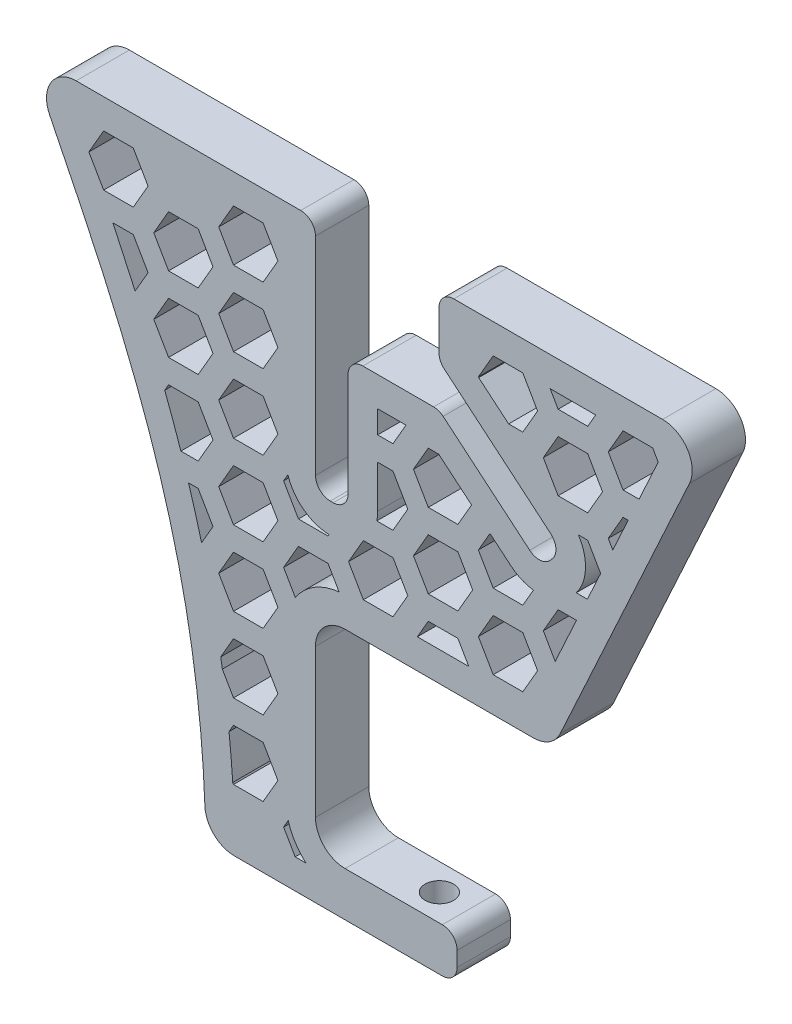
SolidWorks part; units mm, degrees
ref_plane "Front Plane" through (0, 0, 0) normal (0, 0, 1) x (1, 0, 0)
ref_plane "Top Plane" through (0, 0, 0) normal (0, 1, 0) x (1, 0, 0)
ref_plane "Right Plane" through (0, 0, 0) normal (1, 0, 0) x (0, 0, -1)
sketch "Sketch1" plane through (0, 0, 0) normal (0, 0, 1) x (1, 0, 0)
  line L0 (0, -10) -> (0, -60)
  line L1 (10, 0) -> (73.5896, 0)
  line L2 (82.6764, 5.825) -> (126.325, 100.825)
  line L3 (132.8378, 115) -> (-37.1622, 115) construction
  line L4 (-37.1622, 115) -> (-80.8457, 115)
  line L5 (-37.1622, 115) -> (-37.1622, -85) construction
  line L6 (-27.3578, -85) -> (42.8378, -85)
  line L7 (47.8378, -80) -> (47.8378, -75)
  line L8 (42.8378, -70) -> (10, -70)
  line L9 (80, 0) -> (47.8378, -70) construction
  line L10 (0, 0) -> (-37.1622, 0) construction
  line L11 (-89.8011, 100.5501) -> (-65.055, 50.749) construction
  line L12 (-40.3089, 0.948) -> (-37.3503, -75.3873) construction
  line L13 (0, 110) -> (0, 40)
  line L14 (5, 35) -> (6, 35)
  line L15 (11, 40) -> (11, 75)
  line L16 (16, 80) -> (39.8915, 80)
  line L17 (43.1055, 78.8302) -> (72.3532, 54.2885)
  line L18 (79.3973, 54.9048) -> (80.0401, 55.6708)
  line L19 (79.4238, 62.715) -> (43.4974, 92.8608)
  line L20 (41.7114, 96.691) -> (41.7114, 110)
  line L21 (46.7114, 115) -> (117.2382, 115)
  line L22 (41.7114, 80) -> (0, 115) construction
  line L23 (41.7114, 94.3595) -> (41.7114, 80) construction
  line L24 (-5, 115) -> (-37.1622, 115)
  line L25 (-65.055, 50.749) -> (-40.3089, 0.948) construction
  arc A0 (0, -60) -> (10, -70) centre (10, -60) ccw
  arc A1 (0, -10) -> (10, 0) centre (10, -10) cw
  arc A2 (73.5896, 0) -> (82.6764, 5.825) centre (73.5896, 10) ccw
  arc A3 (-27.3578, -85) -> (-37.3503, -75.3873) centre (-27.3578, -75) cw
  arc A4 (126.325, 100.825) -> (117.2382, 115) centre (117.2382, 105) ccw
  arc A5 (-80.8457, 115) -> (-89.8011, 100.5501) centre (-80.8457, 105) ccw
  arc A6 (42.8378, -85) -> (47.8378, -80) centre (42.8378, -80) ccw
  arc A7 (47.8378, -75) -> (42.8378, -70) centre (42.8378, -75) ccw
  arc A8 (0, 40) -> (5, 35) centre (5, 40) ccw
  arc A9 (6, 35) -> (11, 40) centre (6, 40) ccw
  arc A10 (11, 75) -> (16, 80) centre (16, 75) cw
  arc A11 (80.0401, 55.6708) -> (79.4238, 62.715) centre (76.2099, 58.8848) ccw
  arc A12 (72.3532, 54.2885) -> (79.3973, 54.9048) centre (75.5671, 58.1187) ccw
  arc A13 (39.8915, 80) -> (43.1055, 78.8302) centre (39.8915, 75) cw
  arc A14 (43.4974, 92.8608) -> (41.7114, 96.691) centre (46.7114, 96.691) cw
  arc A15 (41.7114, 110) -> (46.7114, 115) centre (46.7114, 110) cw
  arc A16 (0, 110) -> (-5, 115) centre (-5, 110) ccw
  spline S0 degree 3 poles (-89.8011, 100.5501) (-65.055, 50.749) (-40.3089, 0.948) (-37.3503, -75.3873) knots 0 0 0 0 1 1 1 1
  point P20 (0, 0)
  point P22 (0, 0)
  point P23 (0, 0)
  point P26 (0, -70)
  point P44 (47.8378, -85)
  point P50 (0, 35)
  point P53 (11, 35)
  point P56 (11, 80)
  point P59 (83.254, 59.501)
  point P62 (76.1834, 51.0746)
  point P71 (41.7114, 115)
  dimension "D13" = 10
  dimension "D2" = 5
  dimension "D1" = 170
  dimension "D3" = 80
  dimension "D4" = 70
  dimension "D5" = 15
  dimension "D8" = 45
  dimension "D9" = 80
  dimension "D10" = 11
  dimension "D11" = 45
  dimension "D12" = 11
extrude "Boss-Extrude1" add sketch "Sketch1" along normal blind 18
sketch "Sketch2" plane through (0, -70, 0) normal (0, 1, 0) x (1, 0, 0)
  line L0 (32.8378, -9) -> (47.8378, -9) construction
  line L1 (47.8378, -18) -> (47.8378, 0) construction
  circle A0 centre (32.8378, -9) radius 4.8
  dimension "D2" = 9.6
  dimension "D1" = 15
extrude "Cut-Extrude1" cut sketch "Sketch2" against normal through all contours A0
sketch "Sketch3" plane through (0, 0, 18) normal (0, 0, 1) x (1, 0, 0)
  line L0 (-144.2621, 20.3782) -> (-149.2621, 29.0385)
  line L1 (-149.2621, 29.0385) -> (-159.2621, 29.0385)
  line L2 (-159.2621, 29.0385) -> (-164.2621, 20.3782)
  line L3 (-164.2621, 20.3782) -> (-159.2621, 11.718)
  line L4 (-159.2621, 11.718) -> (-149.2621, 11.718)
  line L5 (-149.2621, 11.718) -> (-144.2621, 20.3782)
  line L6 (-122.3339, 7.718) -> (-127.3339, 16.3782)
  line L7 (-127.3339, 16.3782) -> (-137.3339, 16.3782)
  line L8 (-137.3339, 16.3782) -> (-142.3339, 7.718)
  line L9 (-142.3339, 7.718) -> (-137.3339, -0.9423)
  line L10 (-137.3339, -0.9423) -> (-127.3339, -0.9423)
  line L11 (-127.3339, -0.9423) -> (-122.3339, 7.718)
  line L12 (-100.4057, -4.9423) -> (-105.4057, 3.718)
  line L13 (-105.4057, 3.718) -> (-115.4057, 3.718)
  line L14 (-115.4057, 3.718) -> (-120.4057, -4.9423)
  line L15 (-120.4057, -4.9423) -> (-115.4057, -13.6025)
  line L16 (-115.4057, -13.6025) -> (-105.4057, -13.6025)
  line L17 (-166.1903, 33.0385) -> (-171.1903, 41.6987)
  line L18 (-171.1903, 41.6987) -> (-181.1903, 41.6987)
  line L19 (-181.1903, 41.6987) -> (-186.1903, 33.0385)
  line L20 (-186.1903, 33.0385) -> (-181.1903, 24.3782)
  line L21 (-181.1903, 24.3782) -> (-171.1903, 24.3782)
  line L22 (-171.1903, 24.3782) -> (-166.1903, 33.0385)
  line L23 (-105.4057, -13.6025) -> (-100.4057, -4.9423)
  line L24 (-78.4775, -17.6025) -> (-83.4775, -8.9423)
  line L25 (-83.4775, -8.9423) -> (-93.4775, -8.9423)
  line L26 (-93.4775, -8.9423) -> (-98.4775, -17.6025)
  line L27 (-98.4775, -17.6025) -> (-93.4775, -26.2628)
  line L28 (-93.4775, -26.2628) -> (-83.4775, -26.2628)
  line L29 (-83.4775, -26.2628) -> (-78.4775, -17.6025)
  line L30 (-56.5493, -30.2628) -> (-61.5493, -21.6025)
  line L31 (-61.5493, -21.6025) -> (-71.5493, -21.6025)
  line L32 (-10, 105) -> (-80.8457, 105)
  line L33 (-27.3578, -75) -> (-3.2288, -75)
  line L34 (-10, -60) -> (-10, -10)
  line L35 (10, 10) -> (73.5896, 10)
  line L36 (73.5896, 10) -> (117.2382, 105)
  line L37 (117.2382, 105) -> (51.7114, 105)
  line L38 (51.7114, 105) -> (51.7114, 99.0226)
  line L39 (51.7114, 99.0226) -> (85.8517, 70.3754)
  line L40 (87.7005, 49.2429) -> (87.0578, 48.4769)
  line L41 (65.9253, 46.6281) -> (38.0717, 70)
  line L42 (38.0717, 70) -> (21, 70)
  line L43 (21, 70) -> (21, 40)
  line L44 (6, 25) -> (5, 25)
  line L45 (-10, 40) -> (-10, 105)
  line L46 (-10, 105) -> (-80.8457, 105)
  line L47 (-27.3578, -75) -> (-3.2288, -75)
  line L48 (-10, -60) -> (-10, -10)
  line L49 (10, 10) -> (73.5896, 10)
  line L50 (73.5896, 10) -> (117.2382, 105)
  line L51 (117.2382, 105) -> (51.7114, 105)
  line L52 (51.7114, 105) -> (51.7114, 99.0226)
  line L53 (51.7114, 99.0226) -> (85.8517, 70.3754)
  line L54 (87.7005, 49.2429) -> (87.0578, 48.4769)
  line L55 (65.9253, 46.6281) -> (38.0717, 70)
  line L56 (38.0717, 70) -> (21, 70)
  line L57 (21, 70) -> (21, 40)
  line L58 (6, 25) -> (5, 25)
  line L59 (-10, 40) -> (-10, 105)
  line L60 (-71.5493, -21.6025) -> (-76.5493, -30.2628)
  line L61 (-76.5493, -30.2628) -> (-71.5493, -38.923)
  line L62 (-71.5493, -38.923) -> (-61.5493, -38.923)
  line L63 (-61.5493, -38.923) -> (-56.5493, -30.2628)
  line L64 (-34.6211, -42.923) -> (-39.6211, -34.2628)
  line L65 (-39.6211, -34.2628) -> (-49.6211, -34.2628)
  line L66 (-49.6211, -34.2628) -> (-54.6211, -42.923)
  line L67 (-54.6211, -42.923) -> (-49.6211, -51.5833)
  line L68 (-49.6211, -51.5833) -> (-39.6211, -51.5833)
  line L69 (-39.6211, -51.5833) -> (-34.6211, -42.923)
  line L70 (-12.6929, -55.5833) -> (-17.6929, -46.923)
  line L71 (-17.6929, -46.923) -> (-27.6929, -46.923)
  line L72 (-27.6929, -46.923) -> (-32.6929, -55.5833)
  line L73 (-32.6929, -55.5833) -> (-27.6929, -64.2436)
  line L74 (-27.6929, -64.2436) -> (-17.6929, -64.2436)
  line L75 (-17.6929, -64.2436) -> (-12.6929, -55.5833)
  line L76 (9.2353, -68.2436) -> (4.2353, -59.5833)
  line L77 (4.2353, -59.5833) -> (-5.7647, -59.5833)
  line L78 (-5.7647, -59.5833) -> (-10.7647, -68.2436)
  line L79 (-10.7647, -68.2436) -> (-5.7647, -76.9038)
  line L80 (-5.7647, -76.9038) -> (4.2353, -76.9038)
  line L81 (4.2353, -76.9038) -> (9.2353, -68.2436)
  line L82 (31.1635, -80.9038) -> (26.1635, -72.2436)
  line L83 (26.1635, -72.2436) -> (16.1635, -72.2436)
  line L84 (16.1635, -72.2436) -> (11.1635, -80.9038)
  line L85 (11.1635, -80.9038) -> (16.1635, -89.5641)
  line L86 (16.1635, -89.5641) -> (26.1635, -89.5641)
  line L87 (26.1635, -89.5641) -> (31.1635, -80.9038)
  line L88 (-122.3339, 33.0385) -> (-127.3339, 41.6987)
  line L89 (-127.3339, 41.6987) -> (-137.3339, 41.6987)
  line L90 (-137.3339, 41.6987) -> (-142.3339, 33.0385)
  line L91 (-142.3339, 33.0385) -> (-137.3339, 24.3782)
  line L92 (-137.3339, 24.3782) -> (-127.3339, 24.3782)
  line L93 (-127.3339, 24.3782) -> (-122.3339, 33.0385)
  line L94 (-100.4057, 20.3782) -> (-105.4057, 29.0385)
  line L95 (-105.4057, 29.0385) -> (-115.4057, 29.0385)
  line L96 (-115.4057, 29.0385) -> (-120.4057, 20.3782)
  line L97 (-120.4057, 20.3782) -> (-115.4057, 11.718)
  line L98 (-115.4057, 11.718) -> (-105.4057, 11.718)
  line L99 (-105.4057, 11.718) -> (-100.4057, 20.3782)
  line L100 (-78.4775, 7.718) -> (-83.4775, 16.3782)
  line L101 (-83.4775, 16.3782) -> (-93.4775, 16.3782)
  line L102 (-93.4775, 16.3782) -> (-98.4775, 7.718)
  line L103 (-98.4775, 7.718) -> (-93.4775, -0.9423)
  line L104 (-93.4775, -0.9423) -> (-83.4775, -0.9423)
  line L105 (-144.2621, 45.6987) -> (-149.2621, 54.359)
  line L106 (-149.2621, 54.359) -> (-159.2621, 54.359)
  line L107 (-159.2621, 54.359) -> (-164.2621, 45.6987)
  line L108 (-164.2621, 45.6987) -> (-159.2621, 37.0385)
  line L109 (-159.2621, 37.0385) -> (-149.2621, 37.0385)
  line L110 (-149.2621, 37.0385) -> (-144.2621, 45.6987)
  line L111 (-83.4775, -0.9423) -> (-78.4775, 7.718)
  line L112 (-56.5493, -4.9423) -> (-61.5493, 3.718)
  line L113 (-61.5493, 3.718) -> (-71.5493, 3.718)
  line L114 (-71.5493, 3.718) -> (-76.5493, -4.9423)
  line L115 (-76.5493, -4.9423) -> (-71.5493, -13.6025)
  line L116 (-71.5493, -13.6025) -> (-61.5493, -13.6025)
  line L117 (-61.5493, -13.6025) -> (-56.5493, -4.9423)
  line L118 (-34.6211, -17.6025) -> (-39.6211, -8.9423)
  line L119 (-39.6211, -8.9423) -> (-49.6211, -8.9423)
  line L120 (-49.6211, -8.9423) -> (-54.6211, -17.6025)
  line L121 (-54.6211, -17.6025) -> (-49.6211, -26.2628)
  line L122 (-49.6211, -26.2628) -> (-39.6211, -26.2628)
  line L123 (-39.6211, -26.2628) -> (-34.6211, -17.6025)
  line L124 (-12.6929, -30.2628) -> (-17.6929, -21.6025)
  line L125 (-17.6929, -21.6025) -> (-27.6929, -21.6025)
  line L126 (-27.6929, -21.6025) -> (-32.6929, -30.2628)
  line L127 (-32.6929, -30.2628) -> (-27.6929, -38.923)
  line L128 (-27.6929, -38.923) -> (-17.6929, -38.923)
  line L129 (-17.6929, -38.923) -> (-12.6929, -30.2628)
  line L130 (9.2353, -42.923) -> (4.2353, -34.2628)
  line L131 (4.2353, -34.2628) -> (-5.7647, -34.2628)
  line L132 (-5.7647, -34.2628) -> (-10.7647, -42.923)
  line L133 (-10.7647, -42.923) -> (-5.7647, -51.5833)
  line L134 (-5.7647, -51.5833) -> (4.2353, -51.5833)
  line L135 (4.2353, -51.5833) -> (9.2353, -42.923)
  line L136 (31.1635, -55.5833) -> (26.1635, -46.923)
  line L137 (26.1635, -46.923) -> (16.1635, -46.923)
  line L138 (16.1635, -46.923) -> (11.1635, -55.5833)
  line L139 (11.1635, -55.5833) -> (16.1635, -64.2436)
  line L140 (16.1635, -64.2436) -> (26.1635, -64.2436)
  line L141 (26.1635, -64.2436) -> (31.1635, -55.5833)
  line L142 (53.0917, -68.2436) -> (48.0917, -59.5833)
  line L143 (48.0917, -59.5833) -> (38.0917, -59.5833)
  line L144 (38.0917, -59.5833) -> (33.0917, -68.2436)
  line L145 (33.0917, -68.2436) -> (38.0917, -76.9038)
  line L146 (38.0917, -76.9038) -> (48.0917, -76.9038)
  line L147 (48.0917, -76.9038) -> (53.0917, -68.2436)
  line L148 (-100.4057, 45.6987) -> (-105.4057, 54.359)
  line L149 (-105.4057, 54.359) -> (-115.4057, 54.359)
  line L150 (-115.4057, 54.359) -> (-120.4057, 45.6987)
  line L151 (-120.4057, 45.6987) -> (-115.4057, 37.0385)
  line L152 (-115.4057, 37.0385) -> (-105.4057, 37.0385)
  line L153 (-105.4057, 37.0385) -> (-100.4057, 45.6987)
  line L154 (-78.4775, 33.0385) -> (-83.4775, 41.6987)
  line L155 (-83.4775, 41.6987) -> (-93.4775, 41.6987)
  line L156 (-93.4775, 41.6987) -> (-98.4775, 33.0385)
  line L157 (-98.4775, 33.0385) -> (-93.4775, 24.3782)
  line L158 (-93.4775, 24.3782) -> (-83.4775, 24.3782)
  line L159 (-83.4775, 24.3782) -> (-78.4775, 33.0385)
  line L160 (-56.5493, 20.3782) -> (-61.5493, 29.0385)
  line L161 (-61.5493, 29.0385) -> (-71.5493, 29.0385)
  line L162 (-71.5493, 29.0385) -> (-76.5493, 20.3782)
  line L163 (-76.5493, 20.3782) -> (-71.5493, 11.718)
  line L164 (-71.5493, 11.718) -> (-61.5493, 11.718)
  line L165 (-122.3339, 58.359) -> (-127.3339, 67.0192)
  line L166 (-127.3339, 67.0192) -> (-137.3339, 67.0192)
  line L167 (-137.3339, 67.0192) -> (-142.3339, 58.359)
  line L168 (-142.3339, 58.359) -> (-137.3339, 49.6987)
  line L169 (-137.3339, 49.6987) -> (-127.3339, 49.6987)
  line L170 (-127.3339, 49.6987) -> (-122.3339, 58.359)
  line L171 (-61.5493, 11.718) -> (-56.5493, 20.3782)
  line L172 (-34.6211, 7.718) -> (-39.6211, 16.3782)
  line L173 (-39.6211, 16.3782) -> (-49.6211, 16.3782)
  line L174 (-49.6211, 16.3782) -> (-54.6211, 7.718)
  line L175 (-54.6211, 7.718) -> (-49.6211, -0.9423)
  line L176 (-49.6211, -0.9423) -> (-39.6211, -0.9423)
  line L177 (-39.6211, -0.9423) -> (-34.6211, 7.718)
  line L178 (-12.6929, -4.9423) -> (-17.6929, 3.718)
  line L179 (-17.6929, 3.718) -> (-27.6929, 3.718)
  line L180 (-27.6929, 3.718) -> (-32.6929, -4.9423)
  line L181 (-32.6929, -4.9423) -> (-27.6929, -13.6025)
  line L182 (-27.6929, -13.6025) -> (-17.6929, -13.6025)
  line L183 (-17.6929, -13.6025) -> (-12.6929, -4.9423)
  line L184 (9.2353, -17.6025) -> (4.2353, -8.9423)
  line L185 (4.2353, -8.9423) -> (-5.7647, -8.9423)
  line L186 (-5.7647, -8.9423) -> (-10.7647, -17.6025)
  line L187 (-10.7647, -17.6025) -> (-5.7647, -26.2628)
  line L188 (-5.7647, -26.2628) -> (4.2353, -26.2628)
  line L189 (4.2353, -26.2628) -> (9.2353, -17.6025)
  line L190 (31.1635, -30.2628) -> (26.1635, -21.6025)
  line L191 (26.1635, -21.6025) -> (16.1635, -21.6025)
  line L192 (16.1635, -21.6025) -> (11.1635, -30.2628)
  line L193 (11.1635, -30.2628) -> (16.1635, -38.923)
  line L194 (16.1635, -38.923) -> (26.1635, -38.923)
  line L195 (26.1635, -38.923) -> (31.1635, -30.2628)
  line L196 (53.0917, -42.923) -> (48.0917, -34.2628)
  line L197 (48.0917, -34.2628) -> (38.0917, -34.2628)
  line L198 (38.0917, -34.2628) -> (33.0917, -42.923)
  line L199 (33.0917, -42.923) -> (38.0917, -51.5833)
  line L200 (38.0917, -51.5833) -> (48.0917, -51.5833)
  line L201 (48.0917, -51.5833) -> (53.0917, -42.923)
  line L202 (75.0199, -55.5833) -> (70.0199, -46.923)
  line L203 (70.0199, -46.923) -> (60.0199, -46.923)
  line L204 (60.0199, -46.923) -> (55.0199, -55.5833)
  line L205 (55.0199, -55.5833) -> (60.0199, -64.2436)
  line L206 (60.0199, -64.2436) -> (70.0199, -64.2436)
  line L207 (70.0199, -64.2436) -> (75.0199, -55.5833)
  line L208 (-78.4775, 58.359) -> (-83.4775, 67.0192)
  line L209 (-83.4775, 67.0192) -> (-93.4775, 67.0192)
  line L210 (-93.4775, 67.0192) -> (-98.4775, 58.359)
  line L211 (-98.4775, 58.359) -> (-93.4775, 49.6987)
  line L212 (-93.4775, 49.6987) -> (-83.4775, 49.6987)
  line L213 (-83.4775, 49.6987) -> (-78.4775, 58.359)
  line L214 (-56.5493, 45.6987) -> (-61.5493, 54.359)
  line L215 (-61.5493, 54.359) -> (-71.5493, 54.359)
  line L216 (-71.5493, 54.359) -> (-76.5493, 45.6987)
  line L217 (-76.5493, 45.6987) -> (-71.5493, 37.0385)
  line L218 (-71.5493, 37.0385) -> (-61.5493, 37.0385)
  line L219 (-61.5493, 37.0385) -> (-56.5493, 45.6987)
  line L220 (-34.6211, 33.0385) -> (-39.6211, 41.6987)
  line L221 (-39.6211, 41.6987) -> (-49.6211, 41.6987)
  line L222 (-49.6211, 41.6987) -> (-54.6211, 33.0385)
  line L223 (-54.6211, 33.0385) -> (-49.6211, 24.3782)
  line L224 (-49.6211, 24.3782) -> (-39.6211, 24.3782)
  line L225 (-100.4057, 71.0192) -> (-105.4057, 79.6795)
  line L226 (-105.4057, 79.6795) -> (-115.4057, 79.6795)
  line L227 (-115.4057, 79.6795) -> (-120.4057, 71.0192)
  line L228 (-120.4057, 71.0192) -> (-115.4057, 62.359)
  line L229 (-115.4057, 62.359) -> (-105.4057, 62.359)
  line L230 (-105.4057, 62.359) -> (-100.4057, 71.0192)
  line L231 (-39.6211, 24.3782) -> (-34.6211, 33.0385)
  line L232 (-12.6929, 20.3782) -> (-17.6929, 29.0385)
  line L233 (-17.6929, 29.0385) -> (-27.6929, 29.0385)
  line L234 (-27.6929, 29.0385) -> (-32.6929, 20.3782)
  line L235 (-32.6929, 20.3782) -> (-27.6929, 11.718)
  line L236 (-27.6929, 11.718) -> (-17.6929, 11.718)
  line L237 (-17.6929, 11.718) -> (-12.6929, 20.3782)
  line L238 (9.2353, 7.718) -> (4.2353, 16.3782)
  line L239 (4.2353, 16.3782) -> (-5.7647, 16.3782)
  line L240 (-5.7647, 16.3782) -> (-10.7647, 7.718)
  line L241 (-10.7647, 7.718) -> (-5.7647, -0.9423)
  line L242 (-5.7647, -0.9423) -> (4.2353, -0.9423)
  line L243 (4.2353, -0.9423) -> (9.2353, 7.718)
  line L244 (31.1635, -4.9423) -> (26.1635, 3.718)
  line L245 (26.1635, 3.718) -> (16.1635, 3.718)
  line L246 (16.1635, 3.718) -> (11.1635, -4.9423)
  line L247 (11.1635, -4.9423) -> (16.1635, -13.6025)
  line L248 (16.1635, -13.6025) -> (26.1635, -13.6025)
  line L249 (26.1635, -13.6025) -> (31.1635, -4.9423)
  line L250 (53.0917, -17.6025) -> (48.0917, -8.9423)
  line L251 (48.0917, -8.9423) -> (38.0917, -8.9423)
  line L252 (38.0917, -8.9423) -> (33.0917, -17.6025)
  line L253 (33.0917, -17.6025) -> (38.0917, -26.2628)
  line L254 (38.0917, -26.2628) -> (48.0917, -26.2628)
  line L255 (48.0917, -26.2628) -> (53.0917, -17.6025)
  line L256 (75.0199, -30.2628) -> (70.0199, -21.6025)
  line L257 (70.0199, -21.6025) -> (60.0199, -21.6025)
  line L258 (60.0199, -21.6025) -> (55.0199, -30.2628)
  line L259 (55.0199, -30.2628) -> (60.0199, -38.923)
  line L260 (60.0199, -38.923) -> (70.0199, -38.923)
  line L261 (70.0199, -38.923) -> (75.0199, -30.2628)
  line L262 (96.9481, -42.923) -> (91.9481, -34.2628)
  line L263 (91.9481, -34.2628) -> (81.9481, -34.2628)
  line L264 (81.9481, -34.2628) -> (76.9481, -42.923)
  line L265 (76.9481, -42.923) -> (81.9481, -51.5833)
  line L266 (81.9481, -51.5833) -> (91.9481, -51.5833)
  line L267 (91.9481, -51.5833) -> (96.9481, -42.923)
  line L268 (-56.5493, 71.0192) -> (-61.5493, 79.6795)
  line L269 (-61.5493, 79.6795) -> (-71.5493, 79.6795)
  line L270 (-71.5493, 79.6795) -> (-76.5493, 71.0192)
  line L271 (-76.5493, 71.0192) -> (-71.5493, 62.359)
  line L272 (-71.5493, 62.359) -> (-61.5493, 62.359)
  line L273 (-61.5493, 62.359) -> (-56.5493, 71.0192)
  line L274 (-34.6211, 58.359) -> (-39.6211, 67.0192)
  line L275 (-39.6211, 67.0192) -> (-49.6211, 67.0192)
  line L276 (-49.6211, 67.0192) -> (-54.6211, 58.359)
  line L277 (-54.6211, 58.359) -> (-49.6211, 49.6987)
  line L278 (-49.6211, 49.6987) -> (-39.6211, 49.6987)
  line L279 (-39.6211, 49.6987) -> (-34.6211, 58.359)
  line L280 (-12.6929, 45.6987) -> (-17.6929, 54.359)
  line L281 (-17.6929, 54.359) -> (-27.6929, 54.359)
  line L282 (-27.6929, 54.359) -> (-32.6929, 45.6987)
  line L283 (-32.6929, 45.6987) -> (-27.6929, 37.0385)
  line L284 (-27.6929, 37.0385) -> (-17.6929, 37.0385)
  line L285 (-78.4775, 83.6795) -> (-83.4775, 92.3397)
  line L286 (-83.4775, 92.3397) -> (-93.4775, 92.3397)
  line L287 (-93.4775, 92.3397) -> (-98.4775, 83.6795)
  line L288 (-98.4775, 83.6795) -> (-93.4775, 75.0192)
  line L289 (-93.4775, 75.0192) -> (-83.4775, 75.0192)
  line L290 (-83.4775, 75.0192) -> (-78.4775, 83.6795)
  line L291 (-17.6929, 37.0385) -> (-12.6929, 45.6987)
  line L292 (9.2353, 33.0385) -> (4.2353, 41.6987)
  line L293 (4.2353, 41.6987) -> (-5.7647, 41.6987)
  line L294 (-5.7647, 41.6987) -> (-10.7647, 33.0385)
  line L295 (-10.7647, 33.0385) -> (-5.7647, 24.3782)
  line L296 (-5.7647, 24.3782) -> (4.2353, 24.3782)
  line L297 (4.2353, 24.3782) -> (9.2353, 33.0385)
  line L298 (31.1635, 20.3782) -> (26.1635, 29.0385)
  line L299 (26.1635, 29.0385) -> (16.1635, 29.0385)
  line L300 (16.1635, 29.0385) -> (11.1635, 20.3782)
  line L301 (11.1635, 20.3782) -> (16.1635, 11.718)
  line L302 (16.1635, 11.718) -> (26.1635, 11.718)
  line L303 (26.1635, 11.718) -> (31.1635, 20.3782)
  line L304 (53.0917, 7.718) -> (48.0917, 16.3782)
  line L305 (48.0917, 16.3782) -> (38.0917, 16.3782)
  line L306 (38.0917, 16.3782) -> (33.0917, 7.718)
  line L307 (33.0917, 7.718) -> (38.0917, -0.9423)
  line L308 (38.0917, -0.9423) -> (48.0917, -0.9423)
  line L309 (48.0917, -0.9423) -> (53.0917, 7.718)
  line L310 (75.0199, -4.9423) -> (70.0199, 3.718)
  line L311 (70.0199, 3.718) -> (60.0199, 3.718)
  line L312 (60.0199, 3.718) -> (55.0199, -4.9423)
  line L313 (55.0199, -4.9423) -> (60.0199, -13.6025)
  line L314 (60.0199, -13.6025) -> (70.0199, -13.6025)
  line L315 (70.0199, -13.6025) -> (75.0199, -4.9423)
  line L316 (96.9481, -17.6025) -> (91.9481, -8.9423)
  line L317 (91.9481, -8.9423) -> (81.9481, -8.9423)
  line L318 (81.9481, -8.9423) -> (76.9481, -17.6025)
  line L319 (76.9481, -17.6025) -> (81.9481, -26.2628)
  line L320 (81.9481, -26.2628) -> (91.9481, -26.2628)
  line L321 (91.9481, -26.2628) -> (96.9481, -17.6025)
  line L322 (118.8763, -30.2628) -> (113.8763, -21.6025)
  line L323 (113.8763, -21.6025) -> (103.8763, -21.6025)
  line L324 (103.8763, -21.6025) -> (98.8763, -30.2628)
  line L325 (98.8763, -30.2628) -> (103.8763, -38.923)
  line L326 (103.8763, -38.923) -> (113.8763, -38.923)
  line L327 (113.8763, -38.923) -> (118.8763, -30.2628)
  line L328 (-34.6211, 83.6795) -> (-39.6211, 92.3397)
  line L329 (-39.6211, 92.3397) -> (-49.6211, 92.3397)
  line L330 (-49.6211, 92.3397) -> (-54.6211, 83.6795)
  line L331 (-54.6211, 83.6795) -> (-49.6211, 75.0192)
  line L332 (-49.6211, 75.0192) -> (-39.6211, 75.0192)
  line L333 (-39.6211, 75.0192) -> (-34.6211, 83.6795)
  line L334 (-12.6929, 71.0192) -> (-17.6929, 79.6795)
  line L335 (-17.6929, 79.6795) -> (-27.6929, 79.6795)
  line L336 (-27.6929, 79.6795) -> (-32.6929, 71.0192)
  line L337 (-32.6929, 71.0192) -> (-27.6929, 62.359)
  line L338 (-27.6929, 62.359) -> (-17.6929, 62.359)
  line L339 (-17.6929, 62.359) -> (-12.6929, 71.0192)
  line L340 (9.2353, 58.359) -> (4.2353, 67.0192)
  line L341 (4.2353, 67.0192) -> (-5.7647, 67.0192)
  line L342 (-5.7647, 67.0192) -> (-10.7647, 58.359)
  line L343 (-10.7647, 58.359) -> (-5.7647, 49.6987)
  line L344 (-5.7647, 49.6987) -> (4.2353, 49.6987)
  line L345 (-56.5493, 96.3397) -> (-61.5493, 105)
  line L346 (-61.5493, 105) -> (-71.5493, 105)
  line L347 (-71.5493, 105) -> (-76.5493, 96.3397)
  line L348 (-76.5493, 96.3397) -> (-71.5493, 87.6795)
  line L349 (-71.5493, 87.6795) -> (-61.5493, 87.6795)
  line L350 (-61.5493, 87.6795) -> (-56.5493, 96.3397)
  line L351 (4.2353, 49.6987) -> (9.2353, 58.359)
  line L352 (31.1635, 45.6987) -> (26.1635, 54.359)
  line L353 (26.1635, 54.359) -> (16.1635, 54.359)
  line L354 (16.1635, 54.359) -> (11.1635, 45.6987)
  line L355 (11.1635, 45.6987) -> (16.1635, 37.0385)
  line L356 (16.1635, 37.0385) -> (26.1635, 37.0385)
  line L357 (26.1635, 37.0385) -> (31.1635, 45.6987)
  line L358 (53.0917, 33.0385) -> (48.0917, 41.6987)
  line L359 (48.0917, 41.6987) -> (38.0917, 41.6987)
  line L360 (38.0917, 41.6987) -> (33.0917, 33.0385)
  line L361 (33.0917, 33.0385) -> (38.0917, 24.3782)
  line L362 (38.0917, 24.3782) -> (48.0917, 24.3782)
  line L363 (48.0917, 24.3782) -> (53.0917, 33.0385)
  line L364 (75.0199, 20.3782) -> (70.0199, 29.0385)
  line L365 (70.0199, 29.0385) -> (60.0199, 29.0385)
  line L366 (60.0199, 29.0385) -> (55.0199, 20.3782)
  line L367 (55.0199, 20.3782) -> (60.0199, 11.718)
  line L368 (60.0199, 11.718) -> (70.0199, 11.718)
  line L369 (70.0199, 11.718) -> (75.0199, 20.3782)
  line L370 (96.9481, 7.718) -> (91.9481, 16.3782)
  line L371 (91.9481, 16.3782) -> (81.9481, 16.3782)
  line L372 (81.9481, 16.3782) -> (76.9481, 7.718)
  line L373 (76.9481, 7.718) -> (81.9481, -0.9423)
  line L374 (81.9481, -0.9423) -> (91.9481, -0.9423)
  line L375 (91.9481, -0.9423) -> (96.9481, 7.718)
  line L376 (118.8763, -4.9423) -> (113.8763, 3.718)
  line L377 (113.8763, 3.718) -> (103.8763, 3.718)
  line L378 (103.8763, 3.718) -> (98.8763, -4.9423)
  line L379 (98.8763, -4.9423) -> (103.8763, -13.6025)
  line L380 (103.8763, -13.6025) -> (113.8763, -13.6025)
  line L381 (113.8763, -13.6025) -> (118.8763, -4.9423)
  line L382 (140.8045, -17.6025) -> (135.8045, -8.9423)
  line L383 (135.8045, -8.9423) -> (125.8045, -8.9423)
  line L384 (125.8045, -8.9423) -> (120.8045, -17.6025)
  line L385 (120.8045, -17.6025) -> (125.8045, -26.2628)
  line L386 (125.8045, -26.2628) -> (135.8045, -26.2628)
  line L387 (135.8045, -26.2628) -> (140.8045, -17.6025)
  line L388 (-12.6929, 96.3397) -> (-17.6929, 105)
  line L389 (-17.6929, 105) -> (-27.6929, 105)
  line L390 (-27.6929, 105) -> (-32.6929, 96.3397)
  line L391 (-32.6929, 96.3397) -> (-27.6929, 87.6795)
  line L392 (-27.6929, 87.6795) -> (-17.6929, 87.6795)
  line L393 (-17.6929, 87.6795) -> (-12.6929, 96.3397)
  line L394 (9.2353, 83.6795) -> (4.2353, 92.3397)
  line L395 (4.2353, 92.3397) -> (-5.7647, 92.3397)
  line L396 (-5.7647, 92.3397) -> (-10.7647, 83.6795)
  line L397 (-10.7647, 83.6795) -> (-5.7647, 75.0192)
  line L398 (-5.7647, 75.0192) -> (4.2353, 75.0192)
  line L399 (4.2353, 75.0192) -> (9.2353, 83.6795)
  line L400 (31.1635, 71.0192) -> (26.1635, 79.6795)
  line L401 (26.1635, 79.6795) -> (16.1635, 79.6795)
  line L402 (16.1635, 79.6795) -> (11.1635, 71.0192)
  line L403 (11.1635, 71.0192) -> (16.1635, 62.359)
  line L404 (16.1635, 62.359) -> (26.1635, 62.359)
  line L405 (-34.6211, 109) -> (-39.6211, 117.6603)
  line L406 (-39.6211, 117.6603) -> (-49.6211, 117.6603)
  line L407 (-49.6211, 117.6603) -> (-54.6211, 109)
  line L408 (-54.6211, 109) -> (-49.6211, 100.3397)
  line L409 (-49.6211, 100.3397) -> (-39.6211, 100.3397)
  line L410 (-39.6211, 100.3397) -> (-34.6211, 109)
  line L411 (26.1635, 62.359) -> (31.1635, 71.0192)
  line L412 (53.0917, 58.359) -> (48.0917, 67.0192)
  line L413 (48.0917, 67.0192) -> (38.0917, 67.0192)
  line L414 (38.0917, 67.0192) -> (33.0917, 58.359)
  line L415 (33.0917, 58.359) -> (38.0917, 49.6987)
  line L416 (38.0917, 49.6987) -> (48.0917, 49.6987)
  line L417 (48.0917, 49.6987) -> (53.0917, 58.359)
  line L418 (75.0199, 45.6987) -> (70.0199, 54.359)
  line L419 (70.0199, 54.359) -> (60.0199, 54.359)
  line L420 (60.0199, 54.359) -> (55.0199, 45.6987)
  line L421 (55.0199, 45.6987) -> (60.0199, 37.0385)
  line L422 (60.0199, 37.0385) -> (70.0199, 37.0385)
  line L423 (70.0199, 37.0385) -> (75.0199, 45.6987)
  line L424 (96.9481, 33.0385) -> (91.9481, 41.6987)
  line L425 (91.9481, 41.6987) -> (81.9481, 41.6987)
  line L426 (81.9481, 41.6987) -> (76.9481, 33.0385)
  line L427 (76.9481, 33.0385) -> (81.9481, 24.3782)
  line L428 (81.9481, 24.3782) -> (91.9481, 24.3782)
  line L429 (91.9481, 24.3782) -> (96.9481, 33.0385)
  line L430 (118.8763, 20.3782) -> (113.8763, 29.0385)
  line L431 (113.8763, 29.0385) -> (103.8763, 29.0385)
  line L432 (103.8763, 29.0385) -> (98.8763, 20.3782)
  line L433 (98.8763, 20.3782) -> (103.8763, 11.718)
  line L434 (103.8763, 11.718) -> (113.8763, 11.718)
  line L435 (113.8763, 11.718) -> (118.8763, 20.3782)
  line L436 (140.8045, 7.718) -> (135.8045, 16.3782)
  line L437 (135.8045, 16.3782) -> (125.8045, 16.3782)
  line L438 (125.8045, 16.3782) -> (120.8045, 7.718)
  line L439 (120.8045, 7.718) -> (125.8045, -0.9423)
  line L440 (125.8045, -0.9423) -> (135.8045, -0.9423)
  line L441 (135.8045, -0.9423) -> (140.8045, 7.718)
  line L442 (162.7327, -4.9423) -> (157.7327, 3.718)
  line L443 (157.7327, 3.718) -> (147.7327, 3.718)
  line L444 (147.7327, 3.718) -> (142.7327, -4.9423)
  line L445 (142.7327, -4.9423) -> (147.7327, -13.6025)
  line L446 (147.7327, -13.6025) -> (157.7327, -13.6025)
  line L447 (157.7327, -13.6025) -> (162.7327, -4.9423)
  line L448 (9.2353, 109) -> (4.2353, 117.6603)
  line L449 (4.2353, 117.6603) -> (-5.7647, 117.6603)
  line L450 (-5.7647, 117.6603) -> (-10.7647, 109)
  line L451 (-10.7647, 109) -> (-5.7647, 100.3397)
  line L452 (-5.7647, 100.3397) -> (4.2353, 100.3397)
  line L453 (4.2353, 100.3397) -> (9.2353, 109)
  line L454 (31.1635, 96.3397) -> (26.1635, 105)
  line L455 (26.1635, 105) -> (16.1635, 105)
  line L456 (16.1635, 105) -> (11.1635, 96.3397)
  line L457 (11.1635, 96.3397) -> (16.1635, 87.6795)
  line L458 (16.1635, 87.6795) -> (26.1635, 87.6795)
  line L459 (26.1635, 87.6795) -> (31.1635, 96.3397)
  line L460 (53.0917, 83.6795) -> (48.0917, 92.3397)
  line L461 (48.0917, 92.3397) -> (38.0917, 92.3397)
  line L462 (38.0917, 92.3397) -> (33.0917, 83.6795)
  line L463 (33.0917, 83.6795) -> (38.0917, 75.0192)
  line L464 (38.0917, 75.0192) -> (48.0917, 75.0192)
  line L465 (-12.6929, 121.6603) -> (-17.6929, 130.3205)
  line L466 (-17.6929, 130.3205) -> (-27.6929, 130.3205)
  line L467 (-27.6929, 130.3205) -> (-32.6929, 121.6603)
  line L468 (-32.6929, 121.6603) -> (-27.6929, 113)
  line L469 (-27.6929, 113) -> (-17.6929, 113)
  line L470 (-17.6929, 113) -> (-12.6929, 121.6603)
  line L471 (48.0917, 75.0192) -> (53.0917, 83.6795)
  line L472 (75.0199, 71.0192) -> (70.0199, 79.6795)
  line L473 (70.0199, 79.6795) -> (60.0199, 79.6795)
  line L474 (60.0199, 79.6795) -> (55.0199, 71.0192)
  line L475 (55.0199, 71.0192) -> (60.0199, 62.359)
  line L476 (60.0199, 62.359) -> (70.0199, 62.359)
  line L477 (70.0199, 62.359) -> (75.0199, 71.0192)
  line L478 (96.9481, 58.359) -> (91.9481, 67.0192)
  line L479 (91.9481, 67.0192) -> (81.9481, 67.0192)
  line L480 (81.9481, 67.0192) -> (76.9481, 58.359)
  line L481 (76.9481, 58.359) -> (81.9481, 49.6987)
  line L482 (81.9481, 49.6987) -> (91.9481, 49.6987)
  line L483 (91.9481, 49.6987) -> (96.9481, 58.359)
  line L484 (118.8763, 45.6987) -> (113.8763, 54.359)
  line L485 (113.8763, 54.359) -> (103.8763, 54.359)
  line L486 (103.8763, 54.359) -> (98.8763, 45.6987)
  line L487 (98.8763, 45.6987) -> (103.8763, 37.0385)
  line L488 (103.8763, 37.0385) -> (113.8763, 37.0385)
  line L489 (113.8763, 37.0385) -> (118.8763, 45.6987)
  line L490 (140.8045, 33.0385) -> (135.8045, 41.6987)
  line L491 (135.8045, 41.6987) -> (125.8045, 41.6987)
  line L492 (125.8045, 41.6987) -> (120.8045, 33.0385)
  line L493 (120.8045, 33.0385) -> (125.8045, 24.3782)
  line L494 (125.8045, 24.3782) -> (135.8045, 24.3782)
  line L495 (135.8045, 24.3782) -> (140.8045, 33.0385)
  line L496 (162.7327, 20.3782) -> (157.7327, 29.0385)
  line L497 (157.7327, 29.0385) -> (147.7327, 29.0385)
  line L498 (147.7327, 29.0385) -> (142.7327, 20.3782)
  line L499 (142.7327, 20.3782) -> (147.7327, 11.718)
  line L500 (147.7327, 11.718) -> (157.7327, 11.718)
  line L501 (157.7327, 11.718) -> (162.7327, 20.3782)
  line L502 (184.6609, 7.718) -> (179.6609, 16.3782)
  line L503 (179.6609, 16.3782) -> (169.6609, 16.3782)
  line L504 (169.6609, 16.3782) -> (164.6609, 7.718)
  line L505 (164.6609, 7.718) -> (169.6609, -0.9423)
  line L506 (169.6609, -0.9423) -> (179.6609, -0.9423)
  line L507 (179.6609, -0.9423) -> (184.6609, 7.718)
  line L508 (31.1635, 121.6603) -> (26.1635, 130.3205)
  line L509 (26.1635, 130.3205) -> (16.1635, 130.3205)
  line L510 (16.1635, 130.3205) -> (11.1635, 121.6603)
  line L511 (11.1635, 121.6603) -> (16.1635, 113)
  line L512 (16.1635, 113) -> (26.1635, 113)
  line L513 (26.1635, 113) -> (31.1635, 121.6603)
  line L514 (53.0917, 109) -> (48.0917, 117.6603)
  line L515 (48.0917, 117.6603) -> (38.0917, 117.6603)
  line L516 (38.0917, 117.6603) -> (33.0917, 109)
  line L517 (33.0917, 109) -> (38.0917, 100.3397)
  line L518 (38.0917, 100.3397) -> (48.0917, 100.3397)
  line L519 (48.0917, 100.3397) -> (53.0917, 109)
  line L520 (75.0199, 96.3397) -> (70.0199, 105)
  line L521 (70.0199, 105) -> (60.0199, 105)
  line L522 (60.0199, 105) -> (55.0199, 96.3397)
  line L523 (55.0199, 96.3397) -> (60.0199, 87.6795)
  line L524 (60.0199, 87.6795) -> (70.0199, 87.6795)
  line L525 (9.2353, 134.3205) -> (4.2353, 142.9808)
  line L526 (4.2353, 142.9808) -> (-5.7647, 142.9808)
  line L527 (-5.7647, 142.9808) -> (-10.7647, 134.3205)
  line L528 (-10.7647, 134.3205) -> (-5.7647, 125.6603)
  line L529 (-5.7647, 125.6603) -> (4.2353, 125.6603)
  line L530 (4.2353, 125.6603) -> (9.2353, 134.3205)
  line L531 (70.0199, 87.6795) -> (75.0199, 96.3397)
  line L532 (96.9481, 83.6795) -> (91.9481, 92.3397)
  line L533 (91.9481, 92.3397) -> (81.9481, 92.3397)
  line L534 (81.9481, 92.3397) -> (76.9481, 83.6795)
  line L535 (76.9481, 83.6795) -> (81.9481, 75.0192)
  line L536 (81.9481, 75.0192) -> (91.9481, 75.0192)
  line L537 (91.9481, 75.0192) -> (96.9481, 83.6795)
  line L538 (118.8763, 71.0192) -> (113.8763, 79.6795)
  line L539 (113.8763, 79.6795) -> (103.8763, 79.6795)
  line L540 (103.8763, 79.6795) -> (98.8763, 71.0192)
  line L541 (98.8763, 71.0192) -> (103.8763, 62.359)
  line L542 (103.8763, 62.359) -> (113.8763, 62.359)
  line L543 (113.8763, 62.359) -> (118.8763, 71.0192)
  line L544 (140.8045, 58.359) -> (135.8045, 67.0192)
  line L545 (135.8045, 67.0192) -> (125.8045, 67.0192)
  line L546 (125.8045, 67.0192) -> (120.8045, 58.359)
  line L547 (120.8045, 58.359) -> (125.8045, 49.6987)
  line L548 (125.8045, 49.6987) -> (135.8045, 49.6987)
  line L549 (135.8045, 49.6987) -> (140.8045, 58.359)
  line L550 (162.7327, 45.6987) -> (157.7327, 54.359)
  line L551 (157.7327, 54.359) -> (147.7327, 54.359)
  line L552 (147.7327, 54.359) -> (142.7327, 45.6987)
  line L553 (142.7327, 45.6987) -> (147.7327, 37.0385)
  line L554 (147.7327, 37.0385) -> (157.7327, 37.0385)
  line L555 (157.7327, 37.0385) -> (162.7327, 45.6987)
  line L556 (184.6609, 33.0385) -> (179.6609, 41.6987)
  line L557 (179.6609, 41.6987) -> (169.6609, 41.6987)
  line L558 (169.6609, 41.6987) -> (164.6609, 33.0385)
  line L559 (164.6609, 33.0385) -> (169.6609, 24.3782)
  line L560 (169.6609, 24.3782) -> (179.6609, 24.3782)
  line L561 (179.6609, 24.3782) -> (184.6609, 33.0385)
  line L562 (206.5891, 20.3782) -> (201.5891, 29.0385)
  line L563 (201.5891, 29.0385) -> (191.5891, 29.0385)
  line L564 (191.5891, 29.0385) -> (186.5891, 20.3782)
  line L565 (186.5891, 20.3782) -> (191.5891, 11.718)
  line L566 (191.5891, 11.718) -> (201.5891, 11.718)
  line L567 (201.5891, 11.718) -> (206.5891, 20.3782)
  line L568 (53.0917, 134.3205) -> (48.0917, 142.9808)
  line L569 (48.0917, 142.9808) -> (38.0917, 142.9808)
  line L570 (38.0917, 142.9808) -> (33.0917, 134.3205)
  line L571 (33.0917, 134.3205) -> (38.0917, 125.6603)
  line L572 (38.0917, 125.6603) -> (48.0917, 125.6603)
  line L573 (48.0917, 125.6603) -> (53.0917, 134.3205)
  line L574 (75.0199, 121.6603) -> (70.0199, 130.3205)
  line L575 (70.0199, 130.3205) -> (60.0199, 130.3205)
  line L576 (60.0199, 130.3205) -> (55.0199, 121.6603)
  line L577 (55.0199, 121.6603) -> (60.0199, 113)
  line L578 (60.0199, 113) -> (70.0199, 113)
  line L579 (70.0199, 113) -> (75.0199, 121.6603)
  line L580 (96.9481, 109) -> (91.9481, 117.6603)
  line L581 (91.9481, 117.6603) -> (81.9481, 117.6603)
  line L582 (81.9481, 117.6603) -> (76.9481, 109)
  line L583 (76.9481, 109) -> (81.9481, 100.3397)
  line L584 (81.9481, 100.3397) -> (91.9481, 100.3397)
  line L585 (31.1635, 146.9808) -> (26.1635, 155.641)
  line L586 (26.1635, 155.641) -> (16.1635, 155.641)
  line L587 (16.1635, 155.641) -> (11.1635, 146.9808)
  line L588 (11.1635, 146.9808) -> (16.1635, 138.3205)
  line L589 (16.1635, 138.3205) -> (26.1635, 138.3205)
  line L590 (26.1635, 138.3205) -> (31.1635, 146.9808)
  line L591 (91.9481, 100.3397) -> (96.9481, 109)
  line L592 (118.8763, 96.3397) -> (113.8763, 105)
  line L593 (113.8763, 105) -> (103.8763, 105)
  line L594 (103.8763, 105) -> (98.8763, 96.3397)
  line L595 (98.8763, 96.3397) -> (103.8763, 87.6795)
  line L596 (103.8763, 87.6795) -> (113.8763, 87.6795)
  line L597 (113.8763, 87.6795) -> (118.8763, 96.3397)
  line L598 (140.8045, 83.6795) -> (135.8045, 92.3397)
  line L599 (135.8045, 92.3397) -> (125.8045, 92.3397)
  line L600 (125.8045, 92.3397) -> (120.8045, 83.6795)
  line L601 (120.8045, 83.6795) -> (125.8045, 75.0192)
  line L602 (125.8045, 75.0192) -> (135.8045, 75.0192)
  line L603 (135.8045, 75.0192) -> (140.8045, 83.6795)
  line L604 (162.7327, 71.0192) -> (157.7327, 79.6795)
  line L605 (157.7327, 79.6795) -> (147.7327, 79.6795)
  line L606 (147.7327, 79.6795) -> (142.7327, 71.0192)
  line L607 (142.7327, 71.0192) -> (147.7327, 62.359)
  line L608 (147.7327, 62.359) -> (157.7327, 62.359)
  line L609 (157.7327, 62.359) -> (162.7327, 71.0192)
  line L610 (184.6609, 58.359) -> (179.6609, 67.0192)
  line L611 (179.6609, 67.0192) -> (169.6609, 67.0192)
  line L612 (169.6609, 67.0192) -> (164.6609, 58.359)
  line L613 (164.6609, 58.359) -> (169.6609, 49.6987)
  line L614 (169.6609, 49.6987) -> (179.6609, 49.6987)
  line L615 (179.6609, 49.6987) -> (184.6609, 58.359)
  line L616 (206.5891, 45.6987) -> (201.5891, 54.359)
  line L617 (201.5891, 54.359) -> (191.5891, 54.359)
  line L618 (191.5891, 54.359) -> (186.5891, 45.6987)
  line L619 (186.5891, 45.6987) -> (191.5891, 37.0385)
  line L620 (191.5891, 37.0385) -> (201.5891, 37.0385)
  line L621 (201.5891, 37.0385) -> (206.5891, 45.6987)
  line L622 (228.5173, 33.0385) -> (223.5173, 41.6987)
  line L623 (223.5173, 41.6987) -> (213.5173, 41.6987)
  line L624 (213.5173, 41.6987) -> (208.5173, 33.0385)
  line L625 (208.5173, 33.0385) -> (213.5173, 24.3782)
  line L626 (213.5173, 24.3782) -> (223.5173, 24.3782)
  line L627 (223.5173, 24.3782) -> (228.5173, 33.0385)
  circle A0 centre (-154.2621, 20.3782) radius 8.6603 construction
  circle A1 centre (-132.3339, 7.718) radius 8.6603 construction
  circle A2 centre (-110.4057, -4.9423) radius 8.6603 construction
  circle A3 centre (-88.4775, -17.6025) radius 8.6603 construction
  circle A4 centre (-66.5493, -30.2628) radius 8.6603 construction
  circle A5 centre (-44.6211, -42.923) radius 8.6603 construction
  circle A6 centre (-22.6929, -55.5833) radius 8.6603 construction
  circle A7 centre (-0.7647, -68.2436) radius 8.6603 construction
  circle A8 centre (21.1635, -80.9038) radius 8.6603 construction
  circle A9 centre (-132.3339, 33.0385) radius 8.6603 construction
  circle A10 centre (-110.4057, 20.3782) radius 8.6603 construction
  circle A11 centre (-88.4775, 7.718) radius 8.6603 construction
  circle A12 centre (-66.5493, -4.9423) radius 8.6603 construction
  circle A13 centre (-154.2621, 45.6987) radius 8.6603 construction
  circle A14 centre (-44.6211, -17.6025) radius 8.6603 construction
  circle A15 centre (-22.6929, -30.2628) radius 8.6603 construction
  circle A16 centre (-0.7647, -42.923) radius 8.6603 construction
  circle A17 centre (-176.1903, 33.0385) radius 8.6603 construction
  circle A18 centre (21.1635, -55.5833) radius 8.6603 construction
  circle A19 centre (43.0917, -68.2436) radius 8.6603 construction
  circle A20 centre (-110.4057, 45.6987) radius 8.6603 construction
  circle A21 centre (-88.4775, 33.0385) radius 8.6603 construction
  circle A22 centre (-66.5493, 20.3782) radius 8.6603 construction
  circle A23 centre (-44.6211, 7.718) radius 8.6603 construction
  circle A24 centre (-132.3339, 58.359) radius 8.6603 construction
  circle A25 centre (-22.6929, -4.9423) radius 8.6603 construction
  circle A26 centre (-0.7647, -17.6025) radius 8.6603 construction
  circle A27 centre (21.1635, -30.2628) radius 8.6603 construction
  circle A28 centre (43.0917, -42.923) radius 8.6603 construction
  circle A29 centre (65.0199, -55.5833) radius 8.6603 construction
  circle A30 centre (-88.4775, 58.359) radius 8.6603 construction
  circle A31 centre (-66.5493, 45.6987) radius 8.6603 construction
  circle A32 centre (-44.6211, 33.0385) radius 8.6603 construction
  circle A33 centre (-22.6929, 20.3782) radius 8.6603 construction
  arc A34 (-10, -60) -> (-3.2288, -75) centre (10, -60) ccw
  arc A35 (10, 10) -> (-10, -10) centre (10, -10) ccw
  arc A36 (87.7005, 49.2429) -> (85.8517, 70.3754) centre (76.2099, 58.8848) ccw
  arc A37 (65.9253, 46.6281) -> (87.0578, 48.4769) centre (75.5671, 58.1187) ccw
  arc A38 (6, 25) -> (21, 40) centre (6, 40) ccw
  arc A39 (-10, 40) -> (5, 25) centre (5, 40) ccw
  arc A40 (-10, -60) -> (-3.2288, -75) centre (10, -60) ccw
  arc A41 (10, 10) -> (-10, -10) centre (10, -10) ccw
  arc A42 (87.7005, 49.2429) -> (85.8517, 70.3754) centre (76.2099, 58.8848) ccw
  arc A43 (65.9253, 46.6281) -> (87.0578, 48.4769) centre (75.5671, 58.1187) ccw
  arc A44 (6, 25) -> (21, 40) centre (6, 40) ccw
  arc A45 (-10, 40) -> (5, 25) centre (5, 40) ccw
  circle A46 centre (-110.4057, 71.0192) radius 8.6603 construction
  circle A47 centre (-0.7647, 7.718) radius 8.6603 construction
  circle A48 centre (21.1635, -4.9423) radius 8.6603 construction
  circle A49 centre (43.0917, -17.6025) radius 8.6603 construction
  circle A50 centre (65.0199, -30.2628) radius 8.6603 construction
  circle A51 centre (86.9481, -42.923) radius 8.6603 construction
  circle A52 centre (-66.5493, 71.0192) radius 8.6603 construction
  circle A53 centre (-44.6211, 58.359) radius 8.6603 construction
  circle A54 centre (-22.6929, 45.6987) radius 8.6603 construction
  circle A55 centre (-0.7647, 33.0385) radius 8.6603 construction
  circle A56 centre (-88.4775, 83.6795) radius 8.6603 construction
  circle A57 centre (21.1635, 20.3782) radius 8.6603 construction
  circle A58 centre (43.0917, 7.718) radius 8.6603 construction
  circle A59 centre (65.0199, -4.9423) radius 8.6603 construction
  circle A60 centre (86.9481, -17.6025) radius 8.6603 construction
  circle A61 centre (108.8763, -30.2628) radius 8.6603 construction
  circle A62 centre (-44.6211, 83.6795) radius 8.6603 construction
  circle A63 centre (-22.6929, 71.0192) radius 8.6603 construction
  circle A64 centre (-0.7647, 58.359) radius 8.6603 construction
  circle A65 centre (21.1635, 45.6987) radius 8.6603 construction
  circle A66 centre (-66.5493, 96.3397) radius 8.6603 construction
  circle A67 centre (43.0917, 33.0385) radius 8.6603 construction
  circle A68 centre (65.0199, 20.3782) radius 8.6603 construction
  circle A69 centre (86.9481, 7.718) radius 8.6603 construction
  circle A70 centre (108.8763, -4.9423) radius 8.6603 construction
  circle A71 centre (130.8045, -17.6025) radius 8.6603 construction
  circle A72 centre (-22.6929, 96.3397) radius 8.6603 construction
  circle A73 centre (-0.7647, 83.6795) radius 8.6603 construction
  circle A74 centre (21.1635, 71.0192) radius 8.6603 construction
  circle A75 centre (43.0917, 58.359) radius 8.6603 construction
  circle A76 centre (-44.6211, 109) radius 8.6603 construction
  circle A77 centre (65.0199, 45.6987) radius 8.6603 construction
  circle A78 centre (86.9481, 33.0385) radius 8.6603 construction
  circle A79 centre (108.8763, 20.3782) radius 8.6603 construction
  circle A80 centre (130.8045, 7.718) radius 8.6603 construction
  circle A81 centre (152.7327, -4.9423) radius 8.6603 construction
  circle A82 centre (-0.7647, 109) radius 8.6603 construction
  circle A83 centre (21.1635, 96.3397) radius 8.6603 construction
  circle A84 centre (43.0917, 83.6795) radius 8.6603 construction
  circle A85 centre (65.0199, 71.0192) radius 8.6603 construction
  circle A86 centre (-22.6929, 121.6603) radius 8.6603 construction
  circle A87 centre (86.9481, 58.359) radius 8.6603 construction
  circle A88 centre (108.8763, 45.6987) radius 8.6603 construction
  circle A89 centre (130.8045, 33.0385) radius 8.6603 construction
  circle A90 centre (152.7327, 20.3782) radius 8.6603 construction
  circle A91 centre (174.6609, 7.718) radius 8.6603 construction
  circle A92 centre (21.1635, 121.6603) radius 8.6603 construction
  circle A93 centre (43.0917, 109) radius 8.6603 construction
  circle A94 centre (65.0199, 96.3397) radius 8.6603 construction
  circle A95 centre (86.9481, 83.6795) radius 8.6603 construction
  circle A96 centre (-0.7647, 134.3205) radius 8.6603 construction
  circle A97 centre (108.8763, 71.0192) radius 8.6603 construction
  circle A98 centre (130.8045, 58.359) radius 8.6603 construction
  circle A99 centre (152.7327, 45.6987) radius 8.6603 construction
  circle A100 centre (174.6609, 33.0385) radius 8.6603 construction
  circle A101 centre (196.5891, 20.3782) radius 8.6603 construction
  circle A102 centre (43.0917, 134.3205) radius 8.6603 construction
  circle A103 centre (65.0199, 121.6603) radius 8.6603 construction
  circle A104 centre (86.9481, 109) radius 8.6603 construction
  circle A105 centre (108.8763, 96.3397) radius 8.6603 construction
  circle A106 centre (21.1635, 146.9808) radius 8.6603 construction
  circle A107 centre (130.8045, 83.6795) radius 8.6603 construction
  circle A108 centre (152.7327, 71.0192) radius 8.6603 construction
  circle A109 centre (174.6609, 58.359) radius 8.6603 construction
  circle A110 centre (196.5891, 45.6987) radius 8.6603 construction
  circle A111 centre (218.5173, 33.0385) radius 8.6603 construction
  spline S2 degree 3 poles (3039.4272, 2495.8452) (-425.4885, 551.9434) (-195.3759, 342.5058) (-66.9378, 76.6126) (-63.5805, 69.4595) (-57.1643, 55.0134) (-54.1035, 47.7141) (-48.4126, 32.9863) (-45.78, 25.5529) (-41.0098, 10.5247) (-38.8719, 2.9299) (-36.0621, -8.5919) (-35.1913, -12.4554) (-33.5897, -20.1923) (-32.8579, -24.0698) (-30.8655, -35.7286) (-29.8086, -43.5366) (28.3447, -613.3542) (-1231.0225, -1347.0221) (3136.8239, -1346.9386) knots -4.420982 -4.420982 -4.420982 -4.420982 0.125 0.125 0.25 0.25 0.375 0.375 0.5 0.5 0.625 0.625 0.6875 0.6875 0.75 0.75 0.875 0.875 9.833475 9.833475 9.833475 9.833475 only from (-80.8457, 105) to (-27.3578, -75)
  spline S3 degree 3 poles (-80.8457, 105) (-77.3286, 97.922) (-73.812, 90.8437) (-66.9378, 76.6126) (-63.5805, 69.4595) (-57.1643, 55.0134) (-54.1035, 47.7141) (-48.4126, 32.9863) (-45.78, 25.5529) (-41.0098, 10.5247) (-38.8719, 2.9299) (-36.0621, -8.5919) (-35.1913, -12.4554) (-33.5897, -20.1923) (-32.8579, -24.0698) (-30.8655, -35.7286) (-29.8086, -43.5366) (-28.2081, -59.2194) (-27.6642, -67.0942) (-27.3578, -75) knots 0 0 0 0 0.125 0.125 0.25 0.25 0.375 0.375 0.5 0.5 0.625 0.625 0.6875 0.6875 0.75 0.75 0.875 0.875 1 1 1 1
  point P1 (-222.2778, 4.6617)
  point P11 (-212.3902, 27.5828)
  point P829 (-197.1095, 20.8413)
  point P830 (0, 0)
  dimension "D2" = 10
  dimension "D4" = 8
  dimension "D6" = 8
  dimension "D1" = 10
  dimension "D3" = 10
  dimension "D5" = 10
extrude "Cut-Extrude4" cut sketch "Sketch3" against normal through all contours L392 L393 L388 L46 L390 L391 | L349 L350 L345 L46 L347 L348 | L332 L333 L328 L329 L330 L331 | L269 S3 L273 L268 | L338 L339 L334 L335 L336 L337 | L278 L279 L274 L275 L276 L277 | L284 L291 L280 L281 L282 L283 | L222 S3 L224 L231 L220 L221 | L236 L237 L232 L233 L234 L235 | A45 L294 L295 L296 L297 | L173 S3 L177 L172 | L182 L183 L178 L179 L180 L181 | L126 S3 L127 L128 L129 L124 L125 | L72 S3 L73 L74 L75 L70 L71 | A41 L238 L239 L240 L241 | A40 L78 L79 L47 | A44 L300 L301 L302 L303 L298 L299 | A44 L356 L357 L352 L353 L57 | L404 L411 L56 L57 | L416 L417 L55 L413 L414 L415 | L362 L363 L358 L359 L360 L361 | L368 L369 L364 L365 L366 L367 | L305 L306 L49 L304 | A43 L55 L420 L421 L422 L423 | L426 L427 L50 L425 | A42 L482 L50 L478 L479 | L540 L541 L50 L539 | L536 L537 L532 L533 L534 L535 | L524 L531 L520 L51 L522 L523 L53 | L584 L591 L51 L583 | L595 L596 L50 L592 L51 L594
